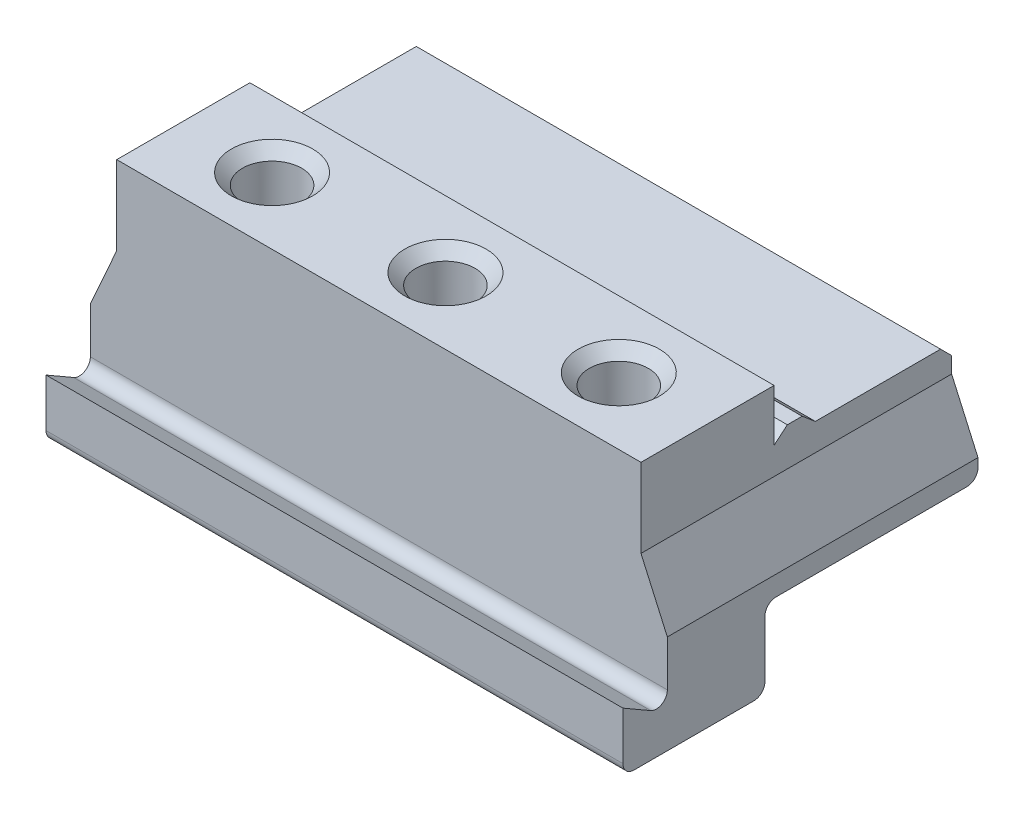
SolidWorks part; units mm, degrees
material "Cast Carbon Steel"
ref_plane "Front Plane" through (0, 0, 0) normal (0, 0, 1) x (1, 0, 0)
ref_plane "Top Plane" through (0, 0, 0) normal (0, 1, 0) x (1, 0, 0)
ref_plane "Right Plane" through (0, 0, 0) normal (1, 0, 0) x (0, 0, -1)
sketch "Sketch1" plane through (0, 0, 0) normal (1, 0, 0) x (0, 0, -1)
  line L1 (0, 8) -> (3.75, 5.8349)
  line L2 (6, 7.134) -> (6, 32)
  line L3 (6, 32) -> (24, 32)
  line L4 (0, 0) -> (48, 0) construction
  line L5 (0, 0) -> (0, 32) construction
  line L6 (0, 32) -> (48, 32) construction
  line L7 (48, 0) -> (48, 32) construction
  line L8 (24, 32) -> (24, 25)
  line L9 (24, 25) -> (25.7876, 26.5)
  line L10 (25.7876, 26.5) -> (27.7876, 26.5)
  line L11 (27.7876, 26.5) -> (29.5753, 25)
  line L12 (29.5753, 25) -> (46.5, 25)
  line L13 (46.5, 25) -> (48, 23.5)
  line L14 (48, 23.5) -> (48, 12.1667)
  line L15 (46.5, 10.6667) -> (20.7, 10.6667)
  line L16 (19.2, 9.1667) -> (19.2, 1.5)
  line L17 (17.7, 0) -> (1.5, 0)
  line L18 (0, 1.5) -> (0, 8)
  arc A0 (3.75, 5.8349) -> (6, 7.134) centre (4.5, 7.134) ccw
  arc A1 (20.7, 10.6667) -> (19.2, 9.1667) centre (20.7, 9.1667) ccw
  arc A2 (19.2, 1.5) -> (17.7, 0) centre (17.7, 1.5) cw
  arc A3 (1.5, 0) -> (0, 1.5) centre (1.5, 1.5) cw
  arc A4 (48, 12.1667) -> (46.5, 10.6667) centre (46.5, 12.1667) cw
  point P35 (48, 10.6667)
  dimension "D3" = 1.5
  dimension "D1" = 32
  dimension "D4" = 6
  dimension "D5" = 120
  dimension "D6" = 8
  dimension "D7" = 18
  dimension "D8" = 45
  dimension "D9" = 50
  dimension "D11" = 7
  dimension "D12" = 2
  dimension "D13" = 1.5
  dimension "D14" = 10.6667
  dimension "D15" = 28.8
  dimension "D10" = 1.5
extrude "Boss-Extrude1" add sketch "Sketch1" along normal blind 78
sketch "Sketch2" plane through (0, 0, 0) normal (0, 0, 1) x (1, 0, 0)
  line L0 (3.5618, 32) -> (3.5618, 21.3333)
  line L1 (78, 32) -> (0, 32) construction
  line L3 (0, 32) -> (0, 7.134) construction
  line L4 (0, 13.3333) -> (0, 32)
  line L5 (0, 32) -> (3.5618, 32)
  line L6 (39, 32) -> (39, 0) construction
  line L7 (78, 0) -> (0, 0) construction
  line L12 (0, 13.3333) -> (3.5618, 21.3333)
  line L13 (78, 13.3333) -> (74.4382, 21.3333)
  line L14 (78, 32) -> (74.4382, 32)
  line L15 (78, 13.3333) -> (78, 32)
  line L16 (74.4382, 32) -> (74.4382, 21.3333)
  dimension "D1" = 8
  dimension "D2" = 10.6667
  dimension "D3" = 24
extrude "Cut-Extrude1" cut sketch "Sketch2" against normal through all both and the other way through all
sketch "Sketch3" plane through (0, 32, 0) normal (0, 1, 0) x (1, 0, 0)
  line L0 (74.4382, 15) -> (3.5618, 15) construction
  line L2 (3.5618, 24) -> (3.5618, 6) construction
  line L3 (15.5618, 15) -> (62.4382, 15) construction
  line L4 (74.4382, 24) -> (74.4382, 6) construction
  circle A0 centre (15.5618, 15) radius 4
  circle A1 centre (62.4382, 15) radius 4
  circle A2 centre (39, 15) radius 4
  point P15 (39, 15)
  dimension "D1" = 8
  dimension "D2" = 12
extrude "Cut-Extrude2" cut sketch "Sketch3" against normal offset from surface 22 and the other way through all up to face at (39, 0, -9.6)
chamfer "Chamfer1" distance 1.5 angle 45 3 edges at (15.5618, 32, -19) (39, 32, -19) (62.4382, 32, -19)
equation "\"C\"= 78"
equation "\"D1@Boss-Extrude1\"=\"C\""
equation "\"A\"= 48"
equation "\"D2@Sketch1\"=\"A\""
equation "\"B\"=32"
equation "\"D1@Sketch1\"=\"B\""
equation "\"D15@Sketch1\"=\"A\"*(3/5)"
equation "\"D14@Sketch1\"=\"B\"/3"
equation "\"D6@Sketch1\"=\"B\"/4"
equation "\"D1@Sketch2\"=\"B\"/4"
equation "\"D2@Sketch2\"=\"B\"/3"
